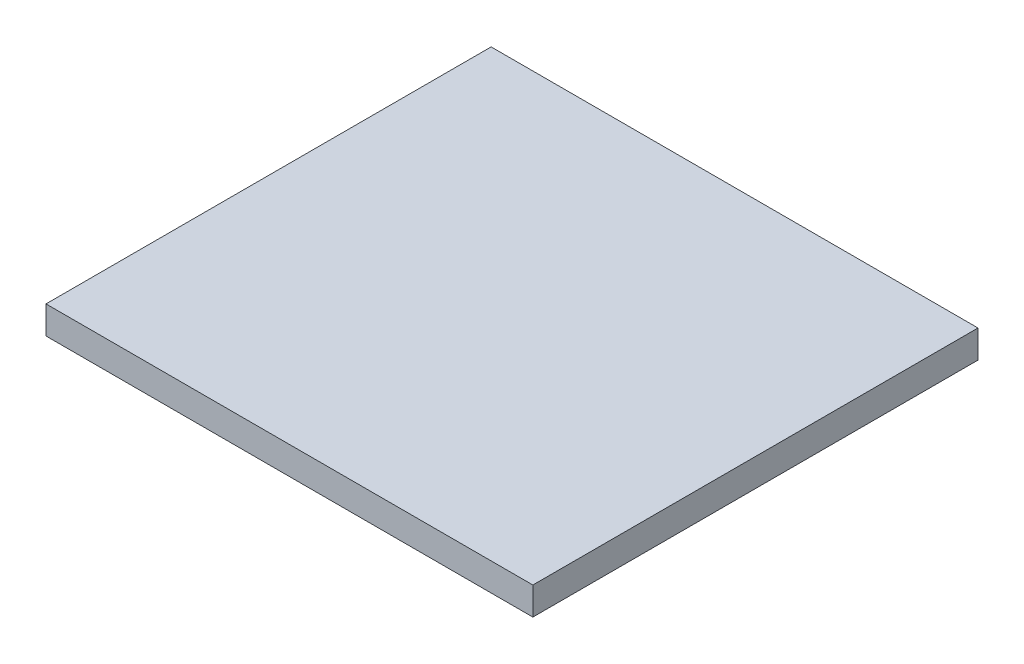
SolidWorks part; units mm, degrees
ref_plane "Front Plane" through (0, 0, 0) normal (0, 0, 1) x (1, 0, 0)
ref_plane "Top Plane" through (0, 0, 0) normal (0, 1, 0) x (1, 0, 0)
ref_plane "Right Plane" through (0, 0, 0) normal (1, 0, 0) x (0, 0, -1)
sketch "Sketch1" plane through (0, 0, 0) normal (0, 0, 1) x (1, 0, 0)
  line L1 (50.1889, 16.1056) -> (67.6889, 16.1056)
  line L2 (50.1889, 16.1056) -> (50.1889, 0.1056)
  line L3 (50.1889, 0.1056) -> (67.6889, 0.1056)
  line L4 (67.6889, 16.1056) -> (67.6889, 0.1056)
  line L5 (58.9389, 0.1056) -> (58.9389, 16.1056) construction
  line L6 (50.1889, 8.1056) -> (67.6889, 8.1056) construction
  point P104 (58.9389, 8.1056)
  dimension "D1" = 16
  dimension "D2" = 17.5
extrude "Boss-Extrude1" add sketch "Sketch1" along normal blind 1
move or copy body "Body-Move/Copy1" bodies to move or copy 102 copy no rotation origin (0, 8.1056, 0.25) rotation axis (1, 0, 0) rotation angle 90
